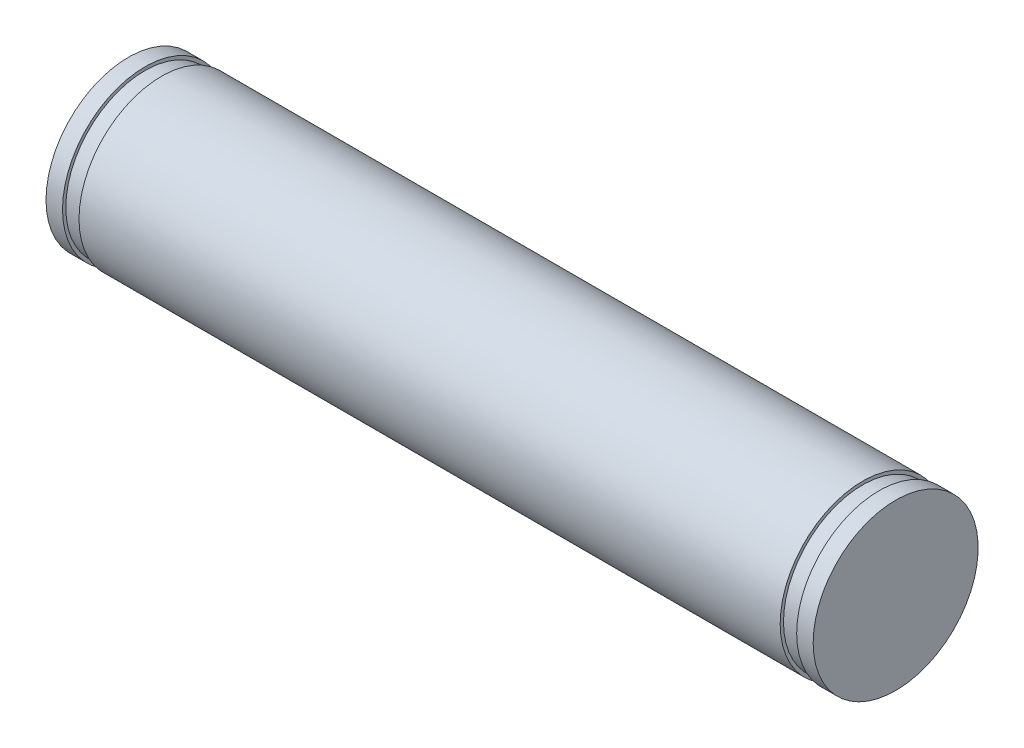
SolidWorks part; units mm, degrees
material "AISI 1020"
ref_plane "Plano superior" through (0, 0, 0) normal (0, 0, 1) x (1, 0, 0)
ref_plane "Plano frontal" through (0, 0, 0) normal (0, 1, 0) x (1, 0, 0)
ref_plane "Plano direito" through (0, 0, 0) normal (1, 0, 0) x (0, 0, -1)
sketch "Esboço1" plane through (0, 0, 0) normal (0, 1, 0) x (1, 0, 0)
  line L0 (-23.25, 0) -> (23.25, 0) construction
  line L1 (-23.25, 0) -> (-23.25, 5)
  line L2 (-23.25, 5) -> (-22.25, 5)
  line L3 (-22.25, 5) -> (-22.25, 4.8)
  line L4 (-22.25, 4.8) -> (-21.25, 4.8)
  line L5 (-21.25, 4.8) -> (-21.25, 5)
  line L6 (-21.25, 5) -> (21.25, 5)
  line L7 (21.25, 5) -> (21.25, 4.8)
  line L8 (21.25, 4.8) -> (22.25, 4.8)
  line L9 (22.25, 4.8) -> (22.25, 5)
  line L10 (22.25, 5) -> (23.25, 5)
  line L11 (23.25, 5) -> (23.25, 0)
  line L12 (-23.25, 0) -> (23.25, 0)
  point P3 (0, 0)
  dimension "D1" = 46.5
  dimension "D2" = 1
  dimension "D3" = 1
  dimension "D4" = 4.8
  dimension "D5" = 5
  dimension "D6" = 1
  dimension "D7" = 1
  dimension "D8" = 4.8
revolve "Revolução1" add sketch "Esboço1" angle 360 about L0
